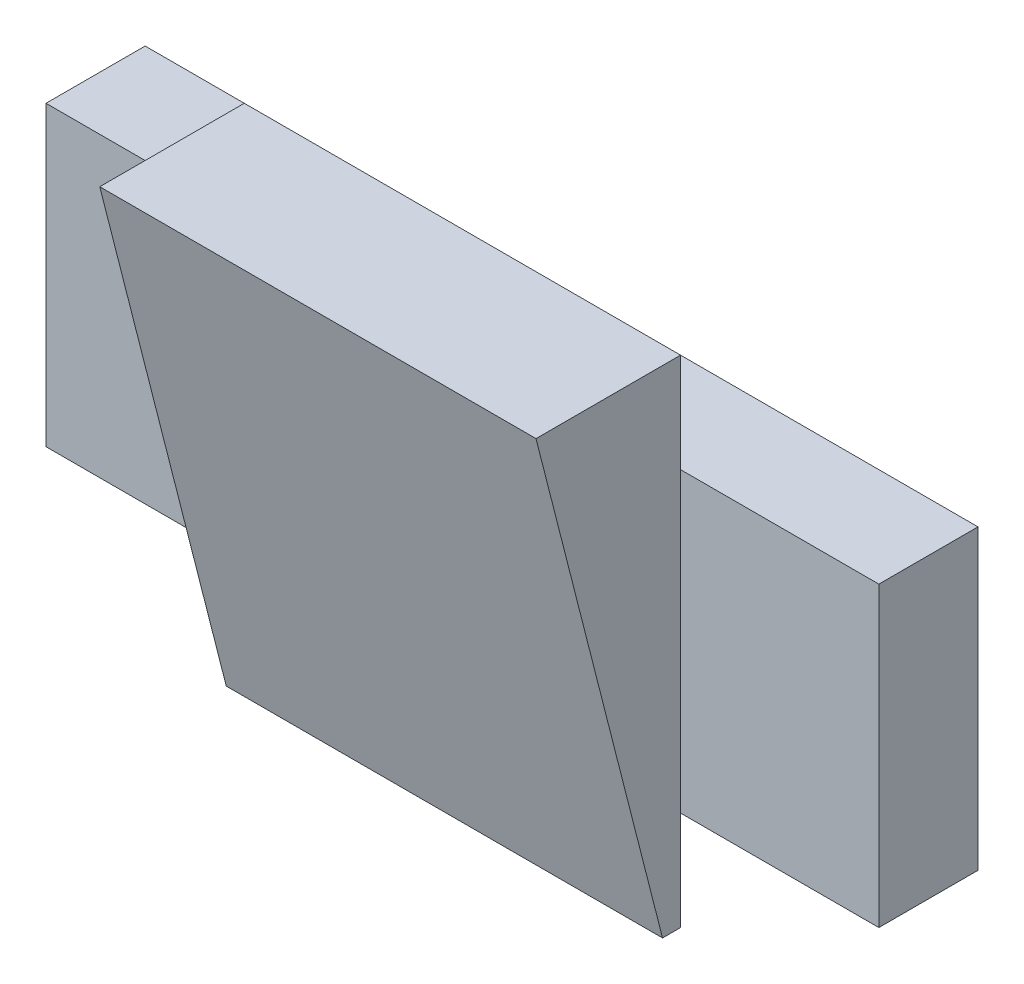
SolidWorks part; units mm, degrees
ref_plane "정면" through (0, 0, 0) normal (0, 0, 1) x (1, 0, 0)
ref_plane "윗면" through (0, 0, 0) normal (0, 1, 0) x (1, 0, 0)
ref_plane "우측면" through (0, 0, 0) normal (1, 0, 0) x (0, 0, -1)
sketch "스케치1" plane through (0, 0, 0) normal (0, 0, 1) x (1, 0, 0)
  line L1 (-21, -7.5) -> (21, -7.5)
  line L2 (-21, -7.5) -> (-21, 7.5)
  line L3 (-21, 7.5) -> (21, 7.5)
  line L4 (21, -7.5) -> (21, 7.5)
  line L5 (-21, -7.5) -> (21, 7.5) construction
  line L6 (-21, 7.5) -> (21, -7.5) construction
  point P0 (0, 0)
  dimension "D1" = 42
  dimension "D2" = 15
extrude "보스-돌출1" add sketch "스케치1" along normal blind 5
sketch "스케치2" plane through (0, 0, 5) normal (0, 0, 1) x (1, 0, 0)
  line L0 (-21, 7.5) -> (-21, -7.5) construction
  line L1 (11, -12.5) -> (-11, -12.5)
  line L2 (11, -12.5) -> (11, 12.5)
  line L3 (11, 12.5) -> (-11, 12.5)
  line L4 (-11, -12.5) -> (-11, 12.5)
  line L5 (11, -12.5) -> (-11, 12.5) construction
  line L6 (11, 12.5) -> (-11, -12.5) construction
  point P0 (0, 0)
  dimension "D1" = 25
  dimension "D2" = 10
extrude "보스-돌출2" add sketch "스케치2" along normal blind 9.5 contours L3 L4 L1 L2
sketch "스케치3" plane through (11, 0, 0) normal (1, 0, 0) x (0, 0, -1)
  line L0 (-12.2894, 12.5) -> (-5.9093, -12.5)
  line L1 (0, -7.5) -> (0, 7.5) construction
  line L2 (-22, 0) -> (-9.8882, 3.091) construction
  line L3 (0, 0) -> (-22, 0) construction
  line L10 (-5, -12.5) -> (-5, -7.5)
  line L11 (-5, -7.5) -> (-5, 7.5)
  line L12 (-5, 7.5) -> (-5, 12.5)
  line L13 (-5, 12.5) -> (-14.5, 12.5)
  line L14 (-14.5, 12.5) -> (-14.5, -12.5)
  line L15 (-14.5, -12.5) -> (-5, -12.5)
  line L19 (-12.2894, 12.5) -> (-14.5, 12.5)
  line L20 (-14.5, 12.5) -> (-14.5, -12.5)
  line L21 (-14.5, -12.5) -> (-5.9093, -12.5)
  point P2 (-22, 0)
  point P5 (0, 0)
  dimension "D1" = 22
  dimension "D2" = 12.5
  dimension "D3" = 0
extrude "컷-돌출1" cut sketch "스케치3" against normal blind 37
